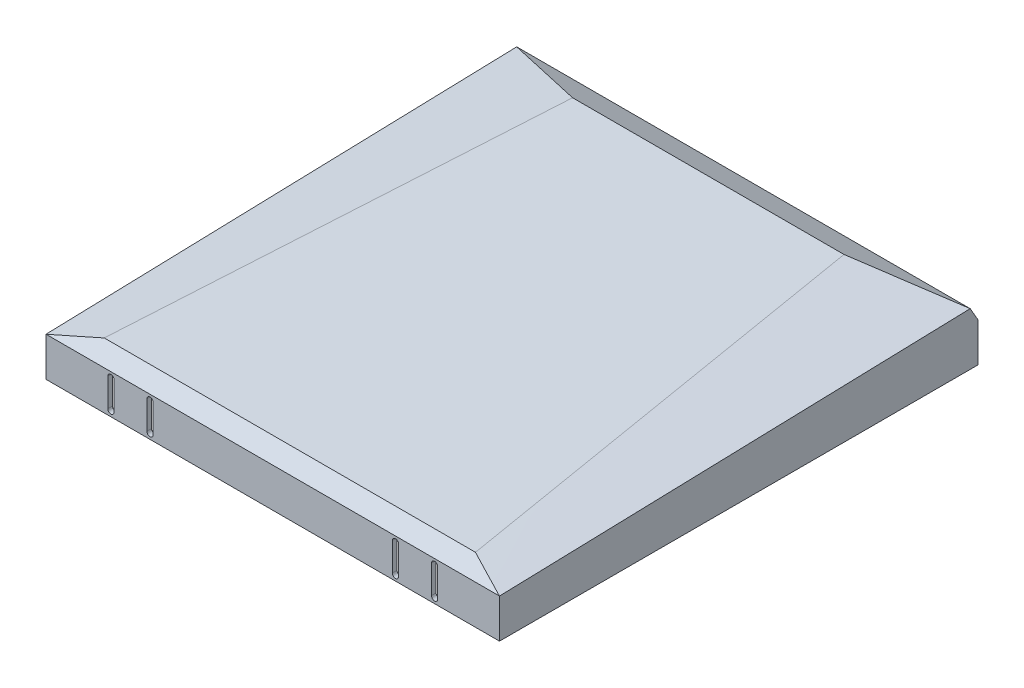
SolidWorks part; units mm, degrees
ref_plane "前视基准面" through (0, 0, 0) normal (0, 0, 1) x (1, 0, 0)
ref_plane "上视基准面" through (0, 0, 0) normal (0, 1, 0) x (1, 0, 0)
ref_plane "右视基准面" through (0, 0, 0) normal (1, 0, 0) x (0, 0, -1)
sketch "草图4" plane through (0, 0, 0) normal (1, 0, 0) x (0, 0, -1)
  line L0 (-148.4783, 0) -> (157.5217, 0)
  line L1 (157.5217, 25) -> (145.0217, 46.6506)
  line L2 (145.0217, 46.6506) -> (-148.4783, 30)
  line L3 (-148.4783, 30) -> (-148.4783, 0)
  line L4 (157.5217, 0) -> (157.5217, 25)
  dimension "D1" = 306
  dimension "D2" = 25
  dimension "D3" = 60
  dimension "D4" = 30
  dimension "D5" = 25
extrude "凸台-拉伸1" add sketch "草图4" along normal mid plane 290
sketch "草图5" plane through (0, 74.4589, -128.9666) normal (0, 0.5, -0.866) x (-1, 0, 0)
  line L0 (-145, -47.1102) -> (-85, -32.1102)
  line L1 (-145, -57.1102) -> (-145, -32.1102) construction
  line L2 (-145, -32.1102) -> (145, -32.1102) construction
  line L3 (-85, -32.1102) -> (-145, -32.1102)
  line L4 (-145, -32.1102) -> (-145, -47.1102)
  dimension "D1" = 60
  dimension "D2" = 15
sketch "草图6" plane through (0, 0, 148.4783) normal (0, 0, 1) x (1, 0, 0)
  line L0 (145, 30) -> (120, 30)
  line L1 (145, 30) -> (-145, 30) construction
  line L2 (120, 30) -> (145, 25)
  line L4 (145, 25) -> (145, 30)
  line L5 (145, 30) -> (145, 0) construction
  line L6 (145, 46.6506) -> (145, 30) construction
  dimension "D1" = 25
  dimension "D2" = 5
loft "切除-放样1" cut profiles "草图5", "草图6"
sketch "草图7" plane through (0, 74.4589, -128.9666) normal (0, 0.5, -0.866) x (-1, 0, 0)
  line L0 (145, -32.1102) -> (85, -32.1102)
  line L1 (-85, -32.1102) -> (145, -32.1102) construction
  line L2 (85, -32.1102) -> (145, -47.1102)
  line L4 (145, -47.1102) -> (145, -32.1102)
  line L5 (145, -57.1102) -> (145, -32.1102) construction
  dimension "D1" = 15
  dimension "D2" = 60
sketch "草图8" plane through (0, 0, 148.4783) normal (0, 0, 1) x (1, 0, 0)
  line L0 (-120, 30) -> (-145, 30)
  line L1 (120, 30) -> (-145, 30) construction
  line L2 (-145, 30) -> (-145, 25)
  line L3 (-145, 30) -> (-145, 0) construction
  line L4 (-145, 25) -> (-120, 30)
  dimension "D1" = 25
  dimension "D2" = 5
loft "切除-放样2" cut profiles "草图7", "草图8"
sketch "草图9" plane through (0, 0, 0) normal (1, 0, 0) x (0, 0, -1)
  line L0 (-148.4783, 25) -> (-137.5424, 30.6204)
  line L1 (145.0217, 46.6506) -> (-148.4783, 30) construction
  line L2 (-137.5424, 30.6204) -> (-148.4783, 30)
  line L3 (-148.4783, 30) -> (-148.4783, 25)
extrude "切除-拉伸1" cut sketch "草图9" against normal mid plane 300
sketch "草图10" plane through (0, 0, 0) normal (1, 0, 0) x (0, 0, -1)
  line L0 (152.5217, 33.6603) -> (130.0458, 45.801)
  line L1 (145.0217, 46.6506) -> (-137.5424, 30.6204) construction
  line L2 (130.0458, 45.801) -> (145.0217, 46.6506)
  line L3 (145.0217, 46.6506) -> (152.5217, 33.6603)
  dimension "D1" = 15
extrude "切除-拉伸2" cut sketch "草图10" against normal mid plane 300
shell "抽壳1" thickness 3
sketch "草图12" plane through (0, 0, 148.4783) normal (0, 0, 1) x (1, 0, 0)
  line L0 (-145, 12.5) -> (145, 12.5) construction
  line L1 (-145, 25) -> (-145, 0) construction
  line L2 (145, 25) -> (145, 0) construction
  line L3 (0, 25) -> (0, 12.5) construction
  line L4 (-145, 25) -> (145, 25) construction
  line L5 (-78.5, 21.5) -> (-78.5, 3.5) construction
  line L6 (-76.5, 21.5) -> (-76.5, 3.5)
  line L7 (-80.5, 21.5) -> (-80.5, 3.5)
  line L8 (-103.5, 21.5) -> (-103.5, 3.5) construction
  line L9 (-101.5, 21.5) -> (-101.5, 3.5)
  line L10 (-105.5, 21.5) -> (-105.5, 3.5)
  line L11 (78.5, 21.5) -> (78.5, 3.5) construction
  line L12 (76.5, 21.5) -> (76.5, 3.5)
  line L13 (80.5, 21.5) -> (80.5, 3.5)
  line L14 (103.5, 21.5) -> (103.5, 3.5) construction
  line L15 (101.5, 21.5) -> (101.5, 3.5)
  line L16 (105.5, 21.5) -> (105.5, 3.5)
  arc A0 (-76.5, 21.5) -> (-80.5, 21.5) centre (-78.5, 21.5) ccw
  arc A1 (-80.5, 3.5) -> (-76.5, 3.5) centre (-78.5, 3.5) ccw
  arc A2 (-101.5, 21.5) -> (-105.5, 21.5) centre (-103.5, 21.5) ccw
  arc A3 (-105.5, 3.5) -> (-101.5, 3.5) centre (-103.5, 3.5) ccw
  arc A4 (76.5, 21.5) -> (80.5, 21.5) centre (78.5, 21.5) cw
  arc A5 (80.5, 3.5) -> (76.5, 3.5) centre (78.5, 3.5) cw
  arc A6 (101.5, 21.5) -> (105.5, 21.5) centre (103.5, 21.5) cw
  arc A7 (105.5, 3.5) -> (101.5, 3.5) centre (103.5, 3.5) cw
  point P12 (-78.5, 12.5)
  point P18 (-103.5, 12.5)
  point P26 (78.5, 12.5)
  point P33 (103.5, 12.5)
  dimension "D1" = 4
  dimension "D2" = 18
  dimension "D3" = 78.5
  dimension "D4" = 25
extrude "切除-拉伸4" cut sketch "草图12" against normal blind 3
sketch "草图13" plane through (0, 0, 0) normal (0, -1, 0) x (1, 0, 0)
  line L0 (145, 148.4783) -> (-145, 148.4783) construction
  line L1 (-142, 145.4783) -> (142, 145.4783)
  line L2 (-142, 145.4783) -> (-142, -154.5217)
  line L3 (-142, -154.5217) -> (142, -154.5217)
  line L4 (142, 145.4783) -> (142, -154.5217)
  line L5 (145, 148.4783) -> (145, -157.5217) construction
  line L7 (-145, 148.4783) -> (-145, -157.5217) construction
  line L9 (145, -157.5217) -> (-145, -157.5217) construction
  dimension "D1" = 3
  dimension "D2" = 3
  dimension "D3" = 3
  dimension "D4" = 3
extrude "切除-拉伸5" cut sketch "草图13" against normal blind 3
sketch "草图14" plane through (0, 0, -157.5217) normal (0, 0, -1) x (-1, 0, 0)
  line L0 (-145, 12) -> (145, 12) construction
  line L1 (-145, 0) -> (-145, 25) construction
  line L2 (145, 0) -> (145, 25) construction
  line L3 (0, 25) -> (0, 0) construction
  line L4 (-145, 25) -> (145, 25) construction
  line L5 (-145, 0) -> (145, 0) construction
  line L6 (-49, 19.5) -> (-49, 4.5) construction
  line L7 (-46.5, 19.5) -> (-46.5, 4.5)
  line L8 (-51.5, 19.5) -> (-51.5, 4.5)
  line L9 (-85, 19.5) -> (-85, 4.5) construction
  line L12 (-82.4543, 19.5) -> (-82.4543, 4.5)
  line L13 (-87.5457, 19.5) -> (-87.5457, 4.5)
  line L14 (49, 19.5) -> (49, 4.5) construction
  line L15 (46.5, 19.5) -> (46.5, 4.5)
  line L16 (51.5, 19.5) -> (51.5, 4.5)
  line L17 (85, 19.5) -> (85, 4.5) construction
  line L18 (82.4543, 19.5) -> (82.4543, 4.5)
  line L19 (87.5457, 19.5) -> (87.5457, 4.5)
  arc A4 (-46.5, 19.5) -> (-51.5, 19.5) centre (-49, 19.5) ccw
  arc A5 (-51.5, 4.5) -> (-46.5, 4.5) centre (-49, 4.5) ccw
  arc A8 (-82.4543, 19.5) -> (-87.5457, 19.5) centre (-85, 19.5) ccw
  arc A9 (-87.5457, 4.5) -> (-82.4543, 4.5) centre (-85, 4.5) ccw
  arc A10 (46.5, 19.5) -> (51.5, 19.5) centre (49, 19.5) cw
  arc A11 (51.5, 4.5) -> (46.5, 4.5) centre (49, 4.5) cw
  arc A12 (82.4543, 19.5) -> (87.5457, 19.5) centre (85, 19.5) cw
  arc A13 (87.5457, 4.5) -> (82.4543, 4.5) centre (85, 4.5) cw
  point P19 (49, 12)
  point P21 (-49, 12)
  point P26 (-85, 12)
  point P38 (85, 12)
  dimension "D2" = 5
  dimension "D1" = 12
  dimension "D3" = 36
  dimension "D4" = 15
  dimension "D5" = 15
  dimension "D6" = 49
extrude "切除-拉伸6" cut sketch "草图14" against normal blind 3
